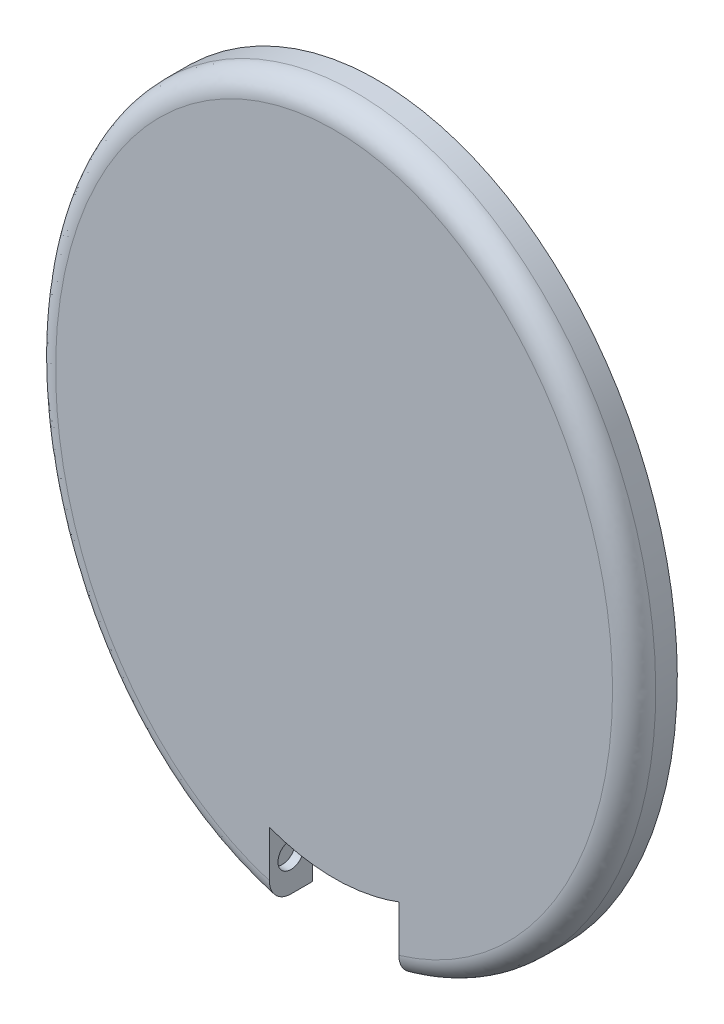
SolidWorks part; units mm, degrees
ref_plane "Front Plane" through (0, 0, 0) normal (0, 0, 1) x (1, 0, 0)
ref_plane "Top Plane" through (0, 0, 0) normal (0, 1, 0) x (1, 0, 0)
ref_plane "Right Plane" through (0, 0, 0) normal (1, 0, 0) x (0, 0, -1)
sketch "Sketch2" plane through (0, 0, 0) normal (0, 0, 1) x (1, 0, 0)
  line L1 (0, 92.4071) -> (0, -70) construction
  ellipse E2 centre (0, 0) end of major axis (0, -85.1542) minor radius 69.503
  ellipse E3 centre (0, 0) end of major axis (0, 70) minor radius 53.9544 (0, 70) -> (0, -70) ccw
  ellipse E4 centre (0, 0) end of major axis (0, -70) minor radius 53.9544
extrude "Boss-Extrude2" add sketch "Sketch2" along normal blind 10
sketch "Sketch5" plane through (0, 0, 0) normal (0, 1, 0) x (1, 0, 0)
  line L0 (0, 0) -> (0, -10) construction
  line L1 (-15, 0) -> (15, 0)
  line L2 (-15, 0) -> (-15, -10)
  line L3 (-15, -10) -> (15, -10)
  line L4 (15, 0) -> (15, -10)
  dimension "D1" = 10
  dimension "D2" = 30
  dimension "D3" = 10
extrude "Cut-Extrude4" cut sketch "Sketch5" against normal blind 198
sketch "Sketch7" plane through (0, 0, 10) normal (0, 0, 1) x (1, 0, 0)
  ellipse E0 centre (0, 0) end of major axis (0, -70) minor radius 53.9544
  ellipse E1 centre (0, 0) end of major axis (0, -70) minor radius 53.9544 construction
extrude "Boss-Extrude4" add sketch "Sketch7" against normal blind 10
fillet "Fillet3" radius 5 1 edges at (0, 85.1542, 10)
sketch "Sketch8" plane through (-15, 0, 0) normal (1, 0, 0) x (0, 0, -1)
  line L0 (-5, -67.2404) -> (-5, -88.4904) construction
  line L1 (0, -67.2404) -> (-10, -67.2404) construction
  circle A0 centre (-5, -75.2404) radius 3
  point P7 (-5, -73.5828)
  dimension "D1" = 8
extrude "Cut-Extrude5" cut sketch "Sketch8" along normal blind 32 and the other way blind 2
